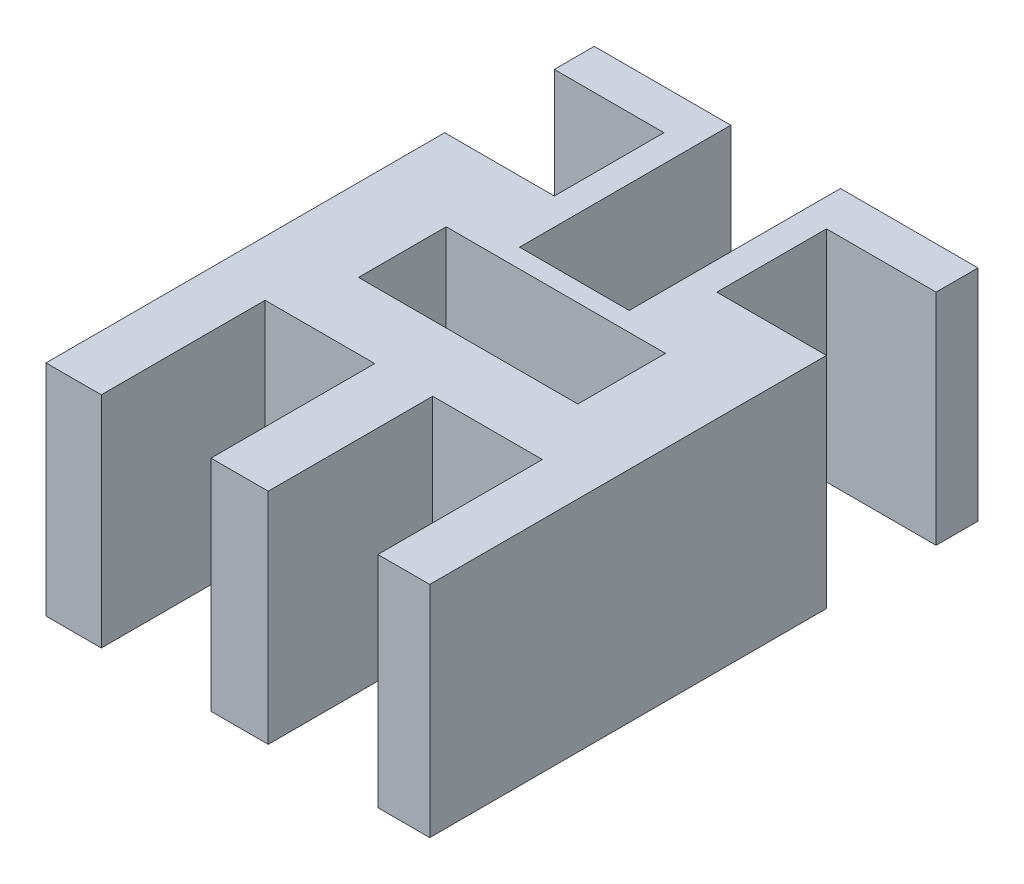
SolidWorks part; units mm, degrees
ref_plane "前视基准面" through (0, 0, 0) normal (0, 0, 1) x (1, 0, 0)
ref_plane "上视基准面" through (0, 0, 0) normal (0, 1, 0) x (1, 0, 0)
ref_plane "右视基准面" through (0, 0, 0) normal (1, 0, 0) x (0, 0, -1)
other "Configuration Table"
sketch "草图1" plane through (0, 0, 0) normal (0, 1, 0) x (1, 0, 0)
  line L1 (-35, 50) -> (35, 50)
  line L2 (-35, 50) -> (-35, -50)
  line L3 (-35, -50) -> (35, -50)
  line L4 (35, 50) -> (35, -50)
  line L5 (-35, 50) -> (35, -50) construction
  line L6 (-35, -50) -> (35, 50) construction
  point P0 (0, 0)
  dimension "D1" = 70
  dimension "D2" = 100
extrude "凸台-拉伸1" add sketch "草图1" along normal blind 40 contours L2 L1 L4 L3
sketch "草图3" plane through (0, 0, 0) normal (0, -1, 0) x (1, 0, 0)
  line L0 (-35, -50) -> (-35, 50) construction
  line L1 (-35, -22.7193) -> (-15, -22.7193)
  line L2 (-35, -22.7193) -> (-35, -42.7193)
  line L3 (-35, -42.7193) -> (-15, -42.7193)
  line L4 (-15, -22.7193) -> (-15, -42.7193)
  line L5 (15.0076, -22.354) -> (35.0076, -22.354)
  line L6 (15.0076, -22.354) -> (15.0076, -42.354)
  line L7 (15.0076, -42.354) -> (35.0076, -42.354)
  line L8 (35.0076, -22.354) -> (35.0076, -42.354)
  dimension "D1" = 20
  dimension "D2" = 20
extrude "切除-拉伸1" cut sketch "草图3" against normal blind 40 contours L5 L8 L7 L6 | L2 L1 L4 L3
sketch "草图5" plane through (0, 40, 0) normal (0, 1, 0) x (1, 0, 0)
  line L0 (-35, -50) -> (35, -50) construction
  line L1 (5.5364, -20) -> (25.5364, -20)
  line L2 (5.5364, -20) -> (5.5364, -50)
  line L3 (5.5364, -50) -> (25.5364, -50)
  line L4 (25.5364, -20) -> (25.5364, -50)
  line L5 (-24.9091, -20.1248) -> (-4.9091, -20.1248)
  line L6 (-24.9091, -20.1248) -> (-24.9091, -50.0423)
  line L7 (-24.9091, -50.0423) -> (-4.9091, -50.0423)
  line L8 (-4.9091, -20.1248) -> (-4.9091, -50.0423)
  dimension "D1" = 20
  dimension "D2" = 30
  dimension "D3" = 20
  dimension "D4" = 29.9174
extrude "切除-拉伸4" cut sketch "草图5" against normal blind 40
sketch "草图13" plane through (0, 40, 0) normal (0, 1, 0) x (1, 0, 0)
  line L1 (-20, 8) -> (20, 8)
  line L2 (-20, 8) -> (-20, -8)
  line L3 (-20, -8) -> (20, -8)
  line L4 (20, 8) -> (20, -8)
  line L5 (-20, 8) -> (20, -8) construction
  line L6 (-20, -8) -> (20, 8) construction
  point P0 (0, 0)
  dimension "D1" = 40
  dimension "D2" = 16
extrude "切除-拉伸5" cut sketch "草图13" against normal blind 40
sketch "草图15" plane through (0, 40, 0) normal (0, 1, 0) x (1, 0, 0)
  line L1 (-10.091, 51.466) -> (9.909, 51.466)
  line L2 (-10.091, 51.466) -> (-10.091, 11.466)
  line L3 (-10.091, 11.466) -> (9.909, 11.466)
  line L4 (9.909, 51.466) -> (9.909, 11.466)
  dimension "D1" = 20
  dimension "D2" = 40
extrude "切除-拉伸6" cut sketch "草图15" against normal blind 40 contours L2 L1 L4 L3
